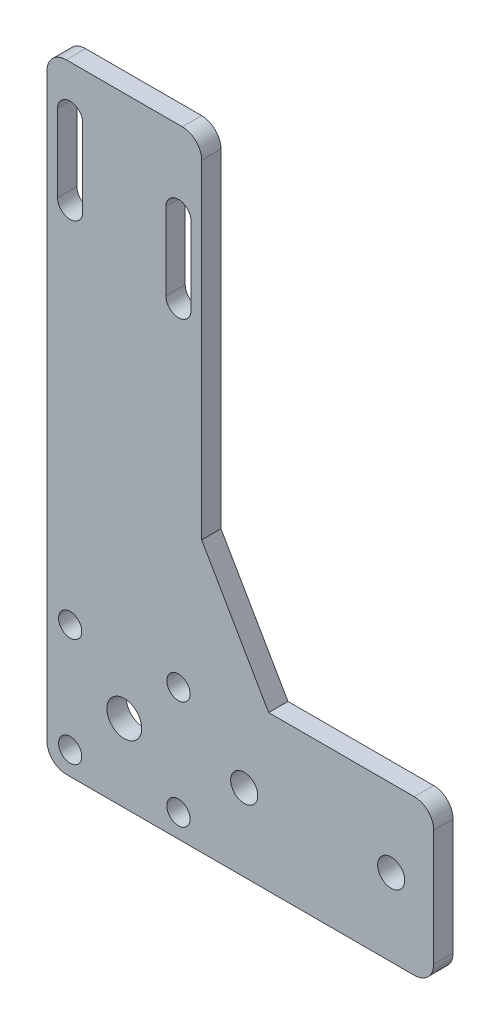
SolidWorks part; units mm, degrees
ref_plane "Front" through (0, 0, 0) normal (0, 0, 1) x (1, 0, 0)
ref_plane "Top" through (0, 0, 0) normal (0, 1, 0) x (1, 0, 0)
ref_plane "Right" through (0, 0, 0) normal (1, 0, 0) x (0, 0, -1)
sketch "Esquisse1" plane through (0, 0, 0) normal (0, 0, 1) x (1, 0, 0)
  line L1 (0, 0) -> (40, 0)
  line L2 (0, 0) -> (0, 160)
  line L3 (0, 160) -> (40, 160)
  line L4 (40, 0) -> (40, 160)
  dimension "D1" = 40
  dimension "D2" = 160
extrude "Boss.-Extru.1" add sketch "Esquisse1" along normal blind 5
sketch "Esquisse2" plane through (0, 0, 5) normal (0, 0, 1) x (1, 0, 0)
  line L0 (20, 0) -> (20, 40) construction
  line L1 (0, 0) -> (40, 0) construction
  line L2 (20, 20) -> (0, 20) construction
  line L3 (0, 160) -> (0, 0) construction
  line L4 (6, 148) -> (6, 128) construction
  line L5 (9.25, 148) -> (9.25, 128)
  line L6 (2.75, 148) -> (2.75, 128)
  line L7 (34, 120) -> (34, 140) construction
  line L8 (30.75, 120) -> (30.75, 140)
  line L9 (37.25, 120) -> (37.25, 140)
  line L10 (37.25, 120) -> (30.75, 120) construction
  line L11 (9.25, 128) -> (2.75, 128) construction
  line L12 (34, 120) -> (34, 34) construction
  circle A0 centre (20, 20) radius 4.5
  circle A1 centre (6, 6) radius 3
  circle A2 centre (34, 6) radius 3
  circle A3 centre (34, 34) radius 3
  circle A4 centre (6, 34) radius 3
  arc A5 (9.25, 148) -> (2.75, 148) centre (6, 148) ccw
  arc A6 (2.75, 128) -> (9.25, 128) centre (6, 128) ccw
  arc A7 (30.75, 120) -> (37.25, 120) centre (34, 120) ccw
  arc A8 (37.25, 140) -> (30.75, 140) centre (34, 140) ccw
  point P19 (6, 138)
  point P26 (34, 130)
  dimension "D2" = 9
  dimension "D3" = 28
  dimension "D4" = 6
  dimension "D5" = 28
  dimension "D6" = 6.5
  dimension "D1" = 40
  dimension "D7" = 20
  dimension "D8" = 118
  dimension "D9" = 20
  dimension "D10" = 110
extrude "Enlèv. mat.-Extru.1" cut sketch "Esquisse2" against normal through all both and the other way through all
sketch "Esquisse3" plane through (0, 0, 5) normal (0, 0, 1) x (1, 0, 0)
  line L0 (40, 20) -> (100, 20) construction
  line L1 (40, 0) -> (100, 0)
  line L2 (40, 0) -> (40, 40)
  line L3 (40, 40) -> (100, 40)
  line L4 (100, 0) -> (100, 40)
  line L5 (70, 20) -> (70, 40) construction
  circle A0 centre (51, 20) radius 3.5
  circle A1 centre (89, 20) radius 3.5
  dimension "D3" = 7
  dimension "D4" = 38
  dimension "D1" = 60
  dimension "D2" = 40
extrude "Boss.-Extru.2" add sketch "Esquisse3" against normal up to vertex (5 mm away)
fillet "Congé1" radius 5 5 edges at (0, 160, 2.5) (40, 160, 2.5) (0, 0, 2.5) (100, 40, 2.5) (100, 0, 2.5)
chamfer "Chanfrein1" distance 30 angle 30 1 edges at (40, 40, 2.5)
